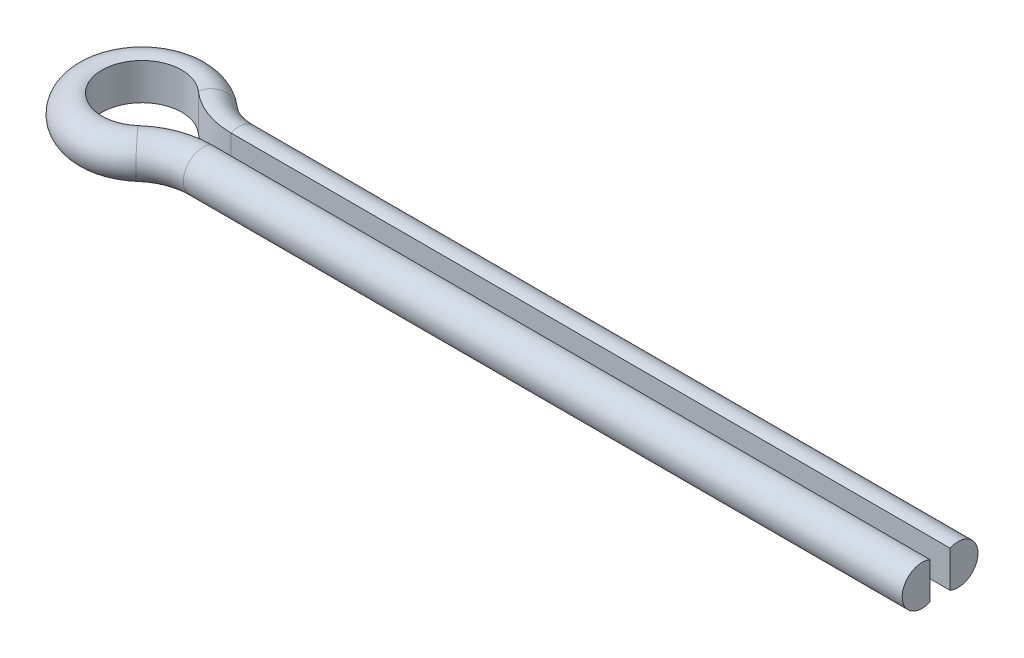
SolidWorks part; units mm, degrees
ref_plane "Front Plane" through (0, 0, 0) normal (0, 0, 1) x (1, 0, 0)
ref_plane "Top Plane" through (0, 0, 0) normal (0, 1, 0) x (1, 0, 0)
ref_plane "Right Plane" through (0, 0, 0) normal (1, 0, 0) x (0, 0, -1)
sketch "Sketch2" plane through (0, 0, 0) normal (0, 1, 0) x (1, 0, 0)
  line L0 (0, 0) -> (100, 0) construction
  line L1 (9.9216, -1.25) -> (100, -1.25)
  line L2 (9.9216, 1.25) -> (100, 1.25)
  arc A0 (3.3072, 3.75) -> (3.3072, -3.75) centre (0, 0) ccw
  arc A1 (3.3072, -3.75) -> (9.9216, -1.25) centre (9.9216, -11.25) cw
  arc A2 (3.3072, 3.75) -> (9.9216, 1.25) centre (9.9216, 11.25) ccw
  point P9 (4.8412, -1.25)
  point P12 (4.8412, 1.25)
  dimension "D1" = 10
  dimension "D4" = 10
  dimension "D5" = 10
  dimension "D2" = 100
  dimension "D3" = 2.5
ref_plane "Plane1" through (100, 0, 0) normal (1, 0, 0) x (0, 0, -1)
sketch "Sketch3" plane through (100, 0, 0) normal (1, 0, 0) x (0, 0, -1)
  line L0 (1.25, 0) -> (4.75, 0) construction
  line L1 (5, 0) -> (-5, 0) construction
  line L2 (4.75, 1.6579) -> (4.75, -1.1333) construction
  line L3 (1.25, 0) -> (1.25, 2.2913)
  line L4 (1.25, 2.2913) -> (1.25, -2.2913)
  arc A0 (1.25, -2.2913) -> (1.25, 2.2913) centre (2.25, 0) ccw
  dimension "D2" = 5
  dimension "D1" = 3.5
sweep "Sweep1" add profiles "Sketch3" path "Sketch2"
